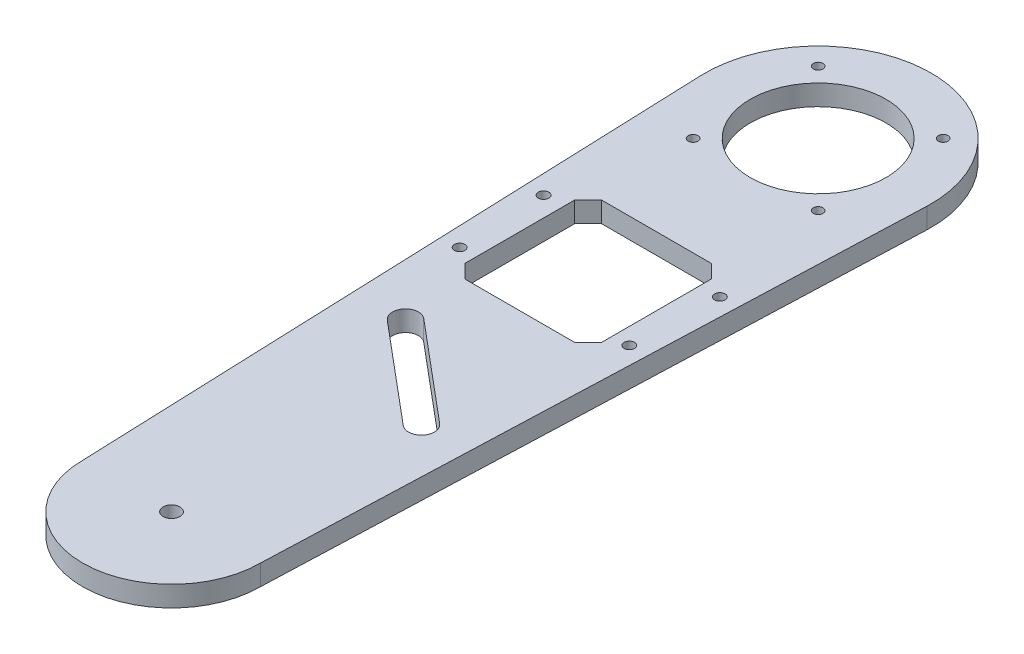
SolidWorks part; units mm, degrees
ref_plane "Front Plane" through (0, 0, 0) normal (0, 0, 1) x (1, 0, 0)
ref_plane "Top Plane" through (0, 0, 0) normal (0, 1, 0) x (1, 0, 0)
ref_plane "Right Plane" through (0, 0, 0) normal (1, 0, 0) x (0, 0, -1)
sketch "Sketch1" plane through (0, 0, 0) normal (0, 1, 0) x (1, 0, 0)
  line L0 (27.5, 0) -> (34.9753, 198.6841)
  line L1 (-27.5, 0) -> (-34.9753, 198.6841)
  arc A0 (-27.5, 0) -> (27.5, 0) centre (0, 0) ccw
  arc A3 (34.9753, 198.6841) -> (-34.9753, 198.6841) centre (0, 200) ccw
  dimension "D1" = 55
  dimension "D3" = 200
  dimension "D2" = 70
extrude "Boss-Extrude1" add sketch "Sketch1" along normal blind 6.35
sketch "Sketch2" plane through (0, 6.35, 0) normal (0, 1, 0) x (1, 0, 0)
  circle A0 centre (0, 0) radius 2.6
  dimension "D1" = 5.2
extrude "Cut-Extrude1" cut sketch "Sketch2" against normal through all
sketch "Esquisse4" plane through (0, 6.35, 0) normal (0, 1, 0) x (1, 0, 0)
  circle A0 centre (0, 200) radius 35
  arc A1 (34.9753, 198.6841) -> (-34.9753, 198.6841) centre (0, 200) ccw construction
sketch "Esquisse3" plane through (0, 6.35, 0) normal (0, 1, 0) x (1, 0, 0)
  circle A1 centre (0, 200) radius 21
  dimension "D1" = 42
extrude "Enlèv. mat.-Extru.2" cut sketch "Esquisse3" against normal through all
sketch "Esquisse5" plane through (0, 6.35, 0) normal (0, 1, 0) x (1, 0, 0)
  circle A0 centre (0, 200) radius 27.35
  dimension "D1" = 54.7
sketch "Esquisse7" plane through (0, 6.35, 0) normal (0, 1, 0) x (1, 0, 0)
  line L0 (-19.3394, 180.6606) -> (19.3394, 180.6606) construction
  line L1 (19.3394, 180.6606) -> (19.3394, 219.3394) construction
  line L2 (19.3394, 219.3394) -> (-19.3394, 219.3394) construction
  line L3 (-19.3394, 219.3394) -> (-19.3394, 180.6606) construction
  circle A0 centre (-19.3394, 219.3394) radius 1.5
  circle A2 centre (19.3394, 219.3394) radius 1.5
  circle A3 centre (19.3394, 180.6606) radius 1.5
  circle A4 centre (-19.3394, 180.6606) radius 1.5
  circle A5 centre (0, 200) radius 27.35 construction
  point P2 (0, 180.6606)
  dimension "D1" = 3
extrude "Enlèv. mat.-Extru.3" cut sketch "Esquisse7" against normal through all
sketch "Sketch3" plane through (0, 6.35, 0) normal (0, 1, 0) x (1, 0, 0)
  line L0 (21.15, 145.8281) -> (21.15, 111.8719)
  line L1 (21.15, 111.8719) -> (16.9781, 107.7)
  line L2 (16.9781, 107.7) -> (-16.9781, 107.7)
  line L3 (-16.9781, 107.7) -> (-21.15, 111.8719)
  line L5 (-21.15, 145.8281) -> (-16.9781, 150)
  line L6 (-16.9781, 150) -> (16.9781, 150)
  line L7 (16.9781, 150) -> (21.15, 145.8281)
  line L8 (-33.3624, 128.85) -> (44.6173, 128.85) construction
  line L9 (0, 172.7946) -> (0, 110.3908) construction
  line L10 (-21.15, 111.8719) -> (-21.15, 145.8281)
  point P12 (0, 150)
  point P13 (0, 107.7)
  point P14 (21.15, 128.85)
  point P15 (0, 128.85)
  point P21 (0, 141.5927)
  dimension "D1" = 128.85
  dimension "D2" = 5.9
  dimension "D3" = 33.9561
  dimension "D5" = 42.3
extrude "Cut-Extrude2" cut sketch "Sketch3" against normal through all
sketch "Sketch5" plane through (0, 6.35, 0) normal (0, 1, 0) x (1, 0, 0)
  line L0 (-27.2565, 142.3405) -> (-26.2414, 115.3595) construction
  line L2 (-27.5, 0) -> (-34.9753, 198.6841) construction
  line L3 (-21.15, 145.8281) -> (-21.15, 111.8719) construction
  line L4 (-27.2565, 142.3405) -> (-32.8554, 142.3405) construction
  line L5 (-32.8554, 142.3405) -> (-31.8403, 115.3595) construction
  line L6 (-31.8403, 115.3595) -> (-26.2414, 115.3595) construction
  line L7 (-32.3478, 128.85) -> (-21.15, 128.85) construction
  circle A2 centre (-27.2565, 142.3405) radius 1.625
  circle A3 centre (-26.2414, 115.3595) radius 1.625
  point P8 (-21.15, 128.85)
  point P9 (-26.7489, 128.85)
  point P12 (-26.7489, 128.85)
  dimension "D1" = 3.25
  dimension "D2" = 27
extrude "Cut-Extrude3" cut sketch "Sketch5" against normal through all
mirror "Mirror1" about plane through (0, 0, 0) normal (1, 0, 0) of "Cut-Extrude3"
sketch "Sketch8" plane through (0, 6.35, 0) normal (0, 1, 0) x (1, 0, 0)
  line L0 (-15.3209, 87.7) -> (15.3209, 61.9885) construction
  line L1 (-12.7497, 90.7642) -> (17.892, 65.0527)
  line L2 (-17.892, 84.6358) -> (12.7497, 58.9243)
  line L4 (16.9781, 107.7) -> (-16.9781, 107.7) construction
  line L5 (-29.4617, 52.1402) -> (29.4617, 52.1402) construction
  line L6 (-27.5, 0) -> (-34.9753, 198.6841) construction
  line L7 (27.5, 0) -> (34.9753, 198.6841) construction
  arc A0 (-12.7497, 90.7642) -> (-17.892, 84.6358) centre (-15.3209, 87.7) ccw
  arc A1 (12.7497, 58.9243) -> (17.892, 65.0527) centre (15.3209, 61.9885) ccw
  point P2 (0, 74.8442)
  dimension "D3" = 4
  dimension "D1" = 40
  dimension "D2" = 20
  dimension "D5" = 40
extrude "Cut-Extrude5" cut sketch "Sketch8" against normal through all
mirror "Mirror2" [suppressed] about plane through (0, 0, 0) normal (1, 0, 0)
